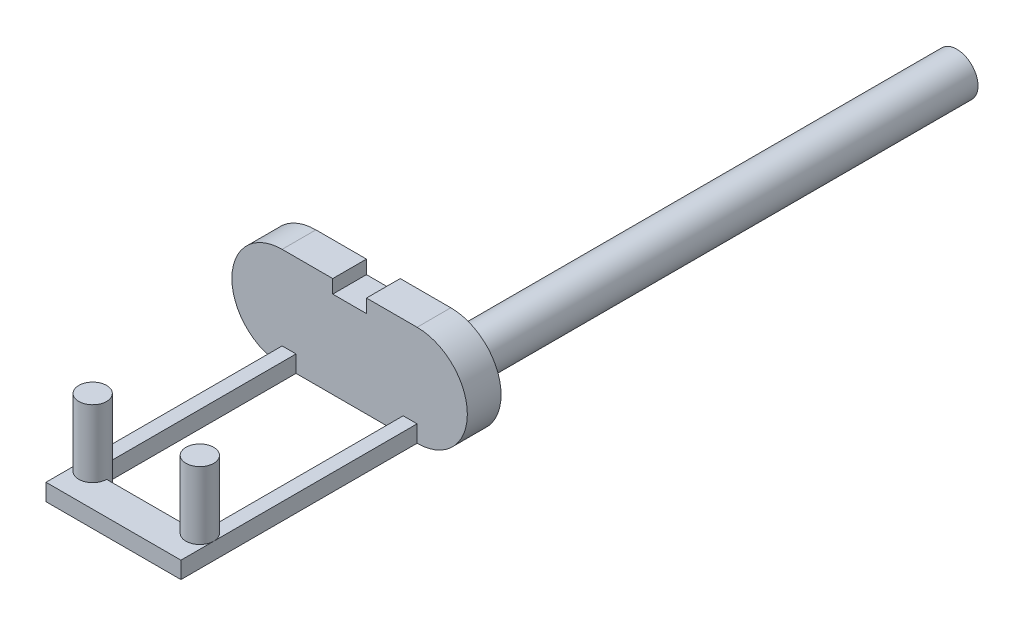
SolidWorks part; units mm, degrees
material "7075-T6 (SN)"
ref_plane "前视基准面" through (0, 0, 0) normal (0, 0, 1) x (1, 0, 0)
ref_plane "上视基准面" through (0, 0, 0) normal (0, 1, 0) x (1, 0, 0)
ref_plane "右视基准面" through (0, 0, 0) normal (1, 0, 0) x (0, 0, -1)
sketch "草图1" plane through (0, 0, 0) normal (0, 0, 1) x (1, 0, 0)
  circle A0 centre (-61.264, 50.3872) radius 3.1354
extrude "凸台-拉伸1" add sketch "草图1" against normal blind 37 and the other way blind 38
sketch "草图2" plane through (0, 0, 38) normal (0, 0, 1) x (1, 0, 0)
  line L0 (-61.264, 50.3872) -> (-81.264, 50.3872) construction
  line L1 (-61.264, 42.9391) -> (-81.264, 42.9391)
  line L2 (-61.264, 57.8353) -> (-81.264, 57.8353)
  arc A0 (-61.264, 42.9391) -> (-61.264, 57.8353) centre (-61.264, 50.3872) ccw
  arc A1 (-81.264, 57.8353) -> (-81.264, 42.9391) centre (-81.264, 50.3872) ccw
  point P2 (-71.264, 50.3872)
  point P7 (-61.264, 50.3872)
  dimension "D1" = 20
extrude "凸台-拉伸2" add sketch "草图2" along normal blind 5
sketch "草图3" plane through (0, 0, 43) normal (0, 0, 1) x (1, 0, 0)
  line L0 (-81.264, 42.9391) -> (-61.264, 42.9391) construction
  line L1 (-81.264, 40.4391) -> (-61.264, 40.4391)
  line L2 (-81.264, 40.4391) -> (-81.264, 45.4391)
  line L3 (-81.264, 45.4391) -> (-61.264, 45.4391)
  line L4 (-61.264, 40.4391) -> (-61.264, 45.4391)
  line L5 (-81.264, 40.4391) -> (-61.264, 45.4391) construction
  line L6 (-81.264, 45.4391) -> (-61.264, 40.4391) construction
  line L7 (-81.264, 42.9391) -> (-61.264, 42.9391)
  line L8 (-79.2048, 40.4391) -> (-63.3232, 40.4391)
  line L9 (-79.2048, 40.4391) -> (-79.2048, 45.4391)
  line L10 (-79.2048, 45.4391) -> (-63.3232, 45.4391)
  line L11 (-63.3232, 40.4391) -> (-63.3232, 45.4391)
  line L12 (-79.2048, 40.4391) -> (-63.3232, 45.4391) construction
  line L13 (-79.2048, 45.4391) -> (-63.3232, 40.4391) construction
  arc A0 (-61.264, 42.9391) -> (-61.264, 57.8353) centre (-61.264, 50.3872) ccw construction
  point P0 (-71.264, 42.9391)
  point P7 (-71.264, 42.9391)
  point P14 (-61.264, 42.9391)
  line M5 (-81.264, 42.9391) -> (-61.264, 42.9391)
  dimension "D1" = 5
extrude "凸台-拉伸3" add sketch "草图3" along normal blind 35 contours L11 L4 L3 M5 | L9 L3 L2 M5
sketch "草图4" plane through (0, 45.4391, 0) normal (0, 1, 0) x (1, 0, 0)
  line L0 (-81.264, -78) -> (-81.264, -43) construction
  line L1 (-61.264, -78) -> (-81.264, -78)
  line L2 (-61.264, -78) -> (-61.264, -73.1395)
  line L3 (-61.264, -73.1395) -> (-81.264, -73.1395)
  line L4 (-81.264, -78) -> (-81.264, -73.1395)
extrude "凸台-拉伸4" add sketch "草图4" against normal up to surface (2.5 mm away) up to face at (-71.264, 42.9391, 56)
sketch "草图5" plane through (0, 45.4391, 0) normal (0, 1, 0) x (1, 0, 0)
  line L0 (-63.3232, -73.1395) -> (-63.3232, -43) construction
  line L1 (-63.3232, -73.1395) -> (-79.2048, -73.1395) construction
  circle A0 centre (-63.3232, -73.1395) radius 2.0592
  circle A1 centre (-79.2048, -73.1395) radius 2.0592
extrude "凸台-拉伸5" add sketch "草图5" along normal blind 10 and the other way up to surface
sketch "草图6" plane through (0, 57.8353, 0) normal (0, 1, 0) x (1, 0, 0)
  line L0 (-61.264, -38) -> (-81.264, -38) construction
  line L1 (-68.764, -30.3857) -> (-73.764, -30.3857)
  line L2 (-68.764, -30.3857) -> (-68.764, -45.6143)
  line L3 (-68.764, -45.6143) -> (-73.764, -45.6143)
  line L4 (-73.764, -30.3857) -> (-73.764, -45.6143)
  line L5 (-68.764, -30.3857) -> (-73.764, -45.6143) construction
  line L6 (-68.764, -45.6143) -> (-73.764, -30.3857) construction
  point P0 (-71.264, -38)
  dimension "D1" = 5
extrude "切除-拉伸1" cut sketch "草图6" against normal blind 2
